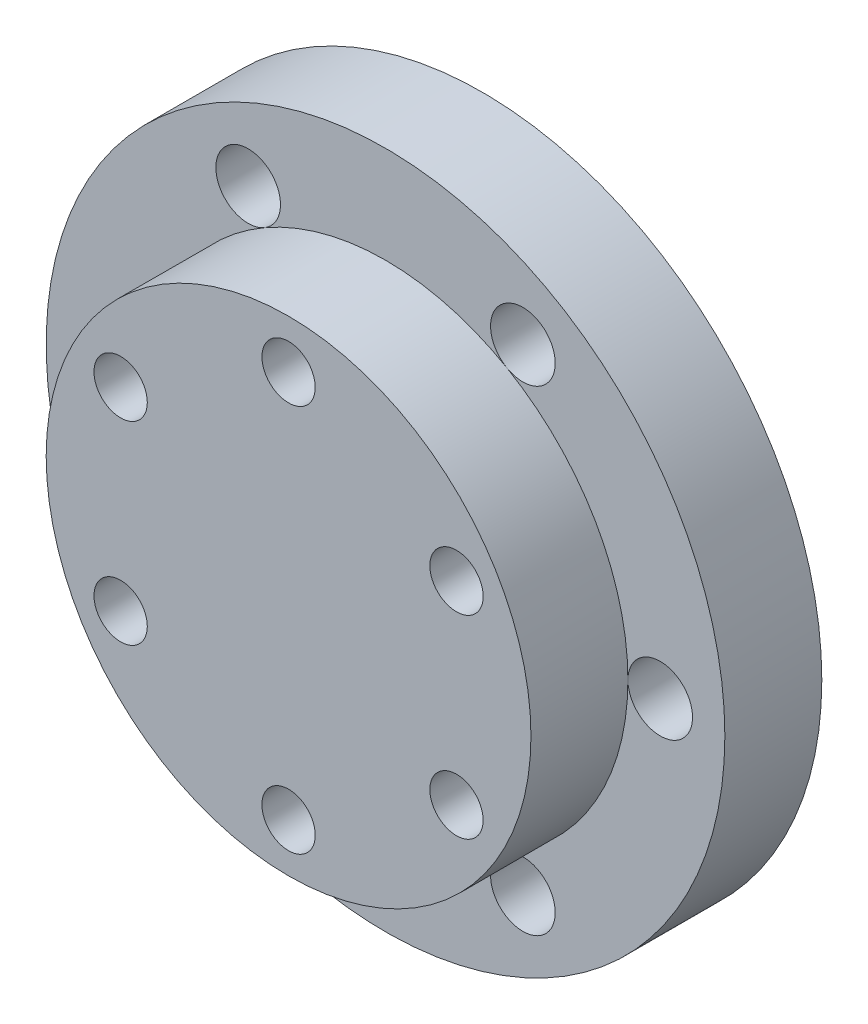
SolidWorks part; units mm, degrees
ref_plane "Front Plane" through (0, 0, 0) normal (1, 0, 0) x (0, 1, 0)
ref_plane "Top Plane" through (0, 0, 0) normal (0, 0, 1) x (0, 1, 0)
ref_plane "Right Plane" through (0, 0, 0) normal (0, 1, 0) x (-1, 0, 0)
sketch "Sketch1" plane through (0, 0, 0) normal (0, 0, 1) x (0, 1, 0)
  circle A0 centre (0, 17) radius 2
  circle A1 centre (14.7224, 8.5) radius 2
  circle A2 centre (14.7224, -8.5) radius 2
  circle A3 centre (0, -17) radius 2
  circle A4 centre (-14.7224, -8.5) radius 2
  circle A5 centre (-14.7224, 8.5) radius 2
  circle A6 centre (0, 0) radius 21
  point P15 (0, 0)
  dimension "D1" = 4
  dimension "D4" = 42
  dimension "D2" = 17
  dimension "D3" = 6
extrude "Boss-Extrude1" add sketch "Sketch1" along normal blind 6
sketch "Sketch2" plane through (0, 0, 6) normal (0, 0, 1) x (1, 0, 0)
  circle A0 centre (0, 0) radius 15
  dimension "D1" = 30
extrude "Boss-Extrude2" add sketch "Sketch2" along normal blind 6 contours A0
sketch "Sketch3" plane through (0, 0, 12) normal (0, 0, 1) x (1, 0, 0)
  circle A0 centre (0, 12) radius 1.65
  circle A1 centre (10.3923, 6) radius 1.65
  circle A2 centre (10.3923, -6) radius 1.65
  circle A3 centre (0, -12) radius 1.65
  circle A4 centre (-10.3923, -6) radius 1.65
  circle A5 centre (-10.3923, 6) radius 1.65
  point P0 (0, 12)
  point P2 (10.3923, 6)
  point P6 (10.3923, -6)
  point P10 (0, -12)
  point P12 (-10.3923, -6)
  point P14 (-10.3923, 6)
  point P16 (0, 0)
  point P17 (0, 0)
  dimension "D2" = 3.3
  dimension "D1" = 12
  dimension "D3" = 6
hole_wizard "Ø3.3 (3.3) Diameter Hole1" positions "3DSketch1" profile "Sketch7" hole size "Ø3.3" standard "ISO"
sketch3d "3DSketch1"
  point P0 (-10.3923, -6, 12)
  point P3 (-10.3923, 6, 12)
  point P6 (0, 12, 12)
  point P9 (10.3923, 6, 12)
  point P12 (10.3923, -6, 12)
  point P15 (0, -12, 12)
sketch "Sketch7" plane through (-10.3923, -6, 12) normal (1, 0, 0) x (0, -1, 0)
  line L0 (0, 0) -> (0, 6.9914)
  line L1 (0, 6.9914) -> (1.65, 6)
  line L2 (1.65, 6) -> (1.65, 0)
  line L5 (1.65, 0) -> (0, 0)
  line L10 (0, 6.9914) -> (-1.65, 6) construction
  line L11 (0, -6.35) -> (0, 107.95) construction
  dimension "Hole Dia." = 3.3
  dimension "Hole Depth" = 6
  dimension "Drill Angle" = 118
thread "Thread1" pitch 0.7 start angle 0, offset 0, length 6, pitch 0.7, diameter 3.3
ref_plane "Plane1" through (-12.0423, 6, 12.7) normal (0, -1, 0) x (-1, 0, 0)
sketch "Thread Profile1" plane through (-12.0423, 6, 12.7) normal (0, -1, 0) x (-1, 0, 0)
  line L0 (0, 0) -> (0, 0.7) construction
  line L1 (0, 0) -> (0.3789, 0.2187)
  line L2 (0.3789, 0.2187) -> (0.3789, 0.3062)
  line L3 (0.3789, 0.3062) -> (0, 0.525)
  line L4 (0.3789, 0.2625) -> (0, 0.2625) construction
  line L11 (0, 0) -> (0, 0.525)
  point P2 (0, 0)
  dimension "Pitch" = 0.7
  dimension "Profile_Angle" = 60
  dimension "Profile_Land" = 0.0875
  dimension "Profile_Height" = 0.3789
sketch "Sketch8" plane through (0, 0, 0) normal (0, 0, -1) x (1, 0, 0)
  circle A0 centre (0, 0) radius 6.35
  point P0 (0, 0)
  dimension "D1" = 12.7
hole_wizard "1/2 (0.5) Diameter Hole1" positions "Sketch8" profile "Sketch9" hole size "1/2" standard "ANSI Inch"
sketch "Sketch9" plane through (0, 0, 0) normal (1, 0, 0) x (0, 1, 0)
  line L0 (0, 0) -> (0, 9.8155)
  line L1 (0, 9.8155) -> (6.35, 6)
  line L2 (6.35, 6) -> (6.35, 0)
  line L5 (6.35, 0) -> (0, 0)
  line L10 (0, 9.8155) -> (-6.35, 6) construction
  line L11 (0, -6.35) -> (0, 107.95) construction
  dimension "Hole Dia." = 12.7
  dimension "Hole Depth" = 6
  dimension "Drill Angle" = 118
